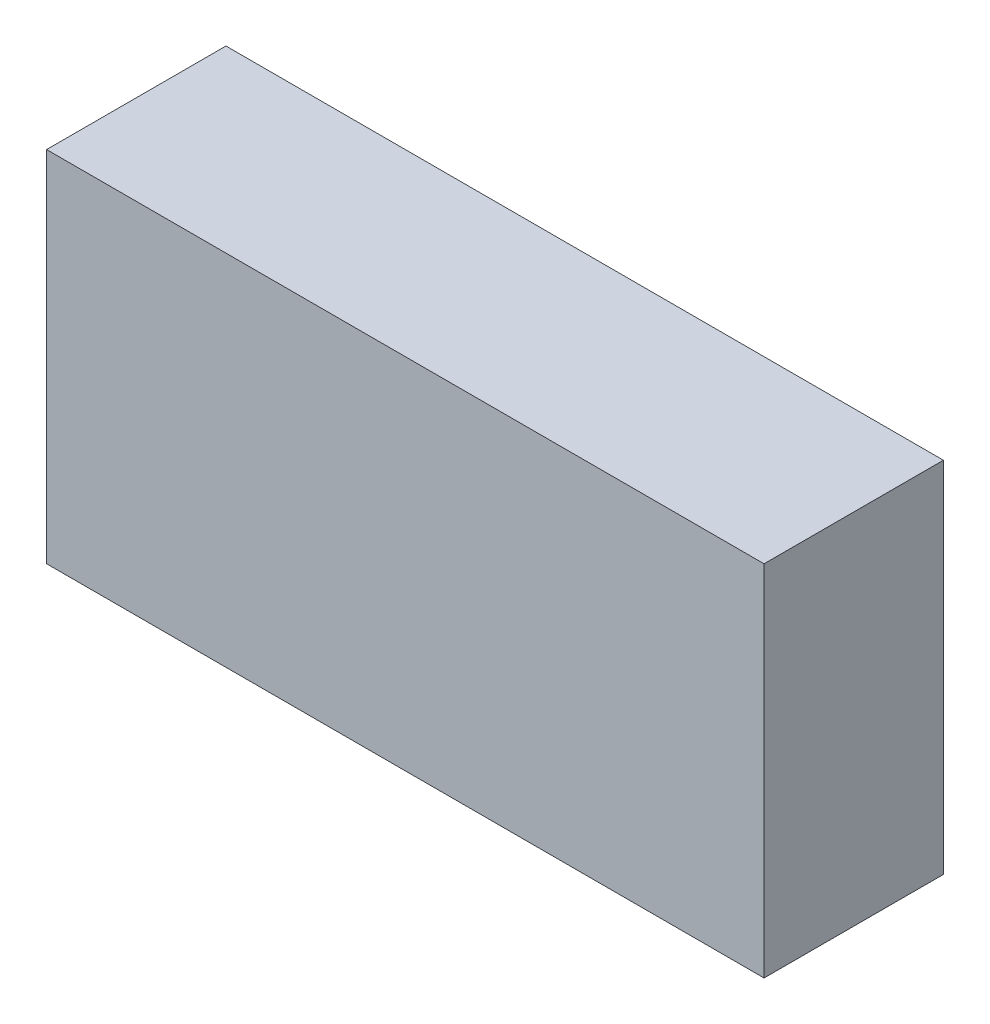
SolidWorks part; units mm, degrees
ref_plane "Front Plane" through (0, 0, 0) normal (0, 0, 1) x (1, 0, 0)
ref_plane "Top Plane" through (0, 0, 0) normal (0, 1, 0) x (1, 0, 0)
ref_plane "Right Plane" through (0, 0, 0) normal (1, 0, 0) x (0, 0, -1)
sketch "Sketch1" plane through (0, 0, 0) normal (0, 0, 1) x (1, 0, 0)
  line L0 (-20, -10) -> (20, -10)
  line L1 (20, -10) -> (20, 10)
  line L2 (20, 10) -> (-20, 10)
  line L3 (-20, 10) -> (-20, -10)
extrude "Boss-Extrude1" add sketch "Sketch1" along normal blind 10
